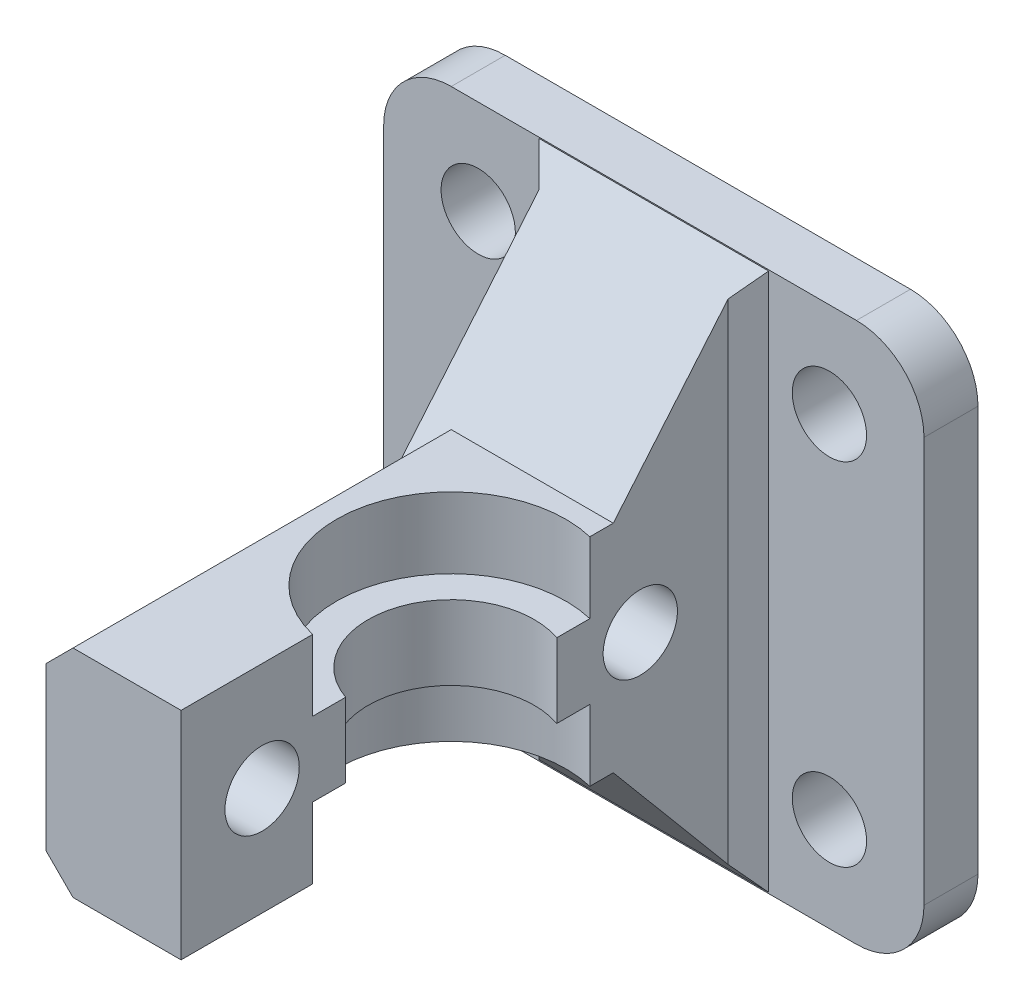
SolidWorks part; units mm, degrees
ref_plane "Front Plane" through (0, 0, 0) normal (0, 0, 1) x (1, 0, 0)
ref_plane "Top Plane" through (0, 0, 0) normal (0, 1, 0) x (1, 0, 0)
ref_plane "Right Plane" through (0, 0, 0) normal (1, 0, 0) x (0, 0, -1)
sketch "Sketch1" plane through (0, 0, 0) normal (0, 0, 1) x (1, 0, 0)
  line L1 (-20, 20) -> (20, 20)
  line L2 (-20, 20) -> (-20, -20)
  line L3 (-20, -20) -> (20, -20)
  line L4 (20, 20) -> (20, -20)
  line L5 (-20, 20) -> (20, -20) construction
  line L6 (-20, -20) -> (20, 20) construction
  point P0 (0, 0)
  dimension "D1" = 40
  dimension "D2" = 40
extrude "Boss-Extrude1" add sketch "Sketch1" along normal blind 4
sketch "Sketch2" plane through (0, 0, 0) normal (0, 0, 1) x (1, 0, 0)
  line L0 (0, 15.4248) -> (0, -21.5401) construction
  line L1 (0, -2.2) -> (0, 2.2) construction
  line L2 (-18.8374, 0) -> (26.7545, 0) construction
  line L3 (2.2, 0) -> (-2.2, 0) construction
  circle A0 centre (-13, 13) radius 2.75
  circle A1 centre (13, 13) radius 2.75
  circle A2 centre (13, -13) radius 2.75
  circle A3 centre (-13, -13) radius 2.75
  dimension "D3" = 5.5
  dimension "D1" = 13
  dimension "D2" = 13
extrude "Cut-Extrude1" cut sketch "Sketch2" along normal up to next
sketch "Sketch3" plane through (0, 0, 0) normal (0, 1, 0) x (1, 0, 0)
  line L0 (-7, -4) -> (-7, -42)
  line L1 (20, -4) -> (-20, -4) construction
  line L2 (-7, -42) -> (3, -42)
  line L3 (0, -21.45) -> (0, 21.45) construction
  line L5 (-7, -4) -> (7, -4)
  line L7 (3, -42) -> (3, -32.2614)
  line L8 (7, -15.7386) -> (7, -4)
  arc A0 (7, -15.7386) -> (3, -32.2614) centre (5, -24) ccw
  dimension "D1" = 8.5
  dimension "D2" = 2
  dimension "D3" = 10
  dimension "D4" = 38
  dimension "D5" = 14
  dimension "D6" = 18
  dimension "D7" = 7
extrude "Boss-Extrude2" add sketch "Sketch3" along normal mid plane 16
chamfer "Chamfer1" distance 10 angle 50 2 edges at (0, -8, 4) (0, 8, 4)
sketch "Sketch4" plane through (0, 0, 0) normal (1, 0, 0) x (0, 0, -1)
  line L0 (22, 0) -> (-22, 0) construction
  line L1 (-4, 19.9175) -> (-4, -19.9175) construction
  circle A0 centre (-12, 0) radius 2.75
  circle A1 centre (-36, 0) radius 2.75
  dimension "D1" = 5.5
  dimension "D2" = 5.5
  dimension "D3" = 8
  dimension "D4" = 32
extrude "Cut-Extrude2" cut sketch "Sketch4" against normal mid plane 14
sketch "Sketch5" plane through (0, 0, 0) normal (0, 1, 0) x (1, 0, 0)
  line L0 (7, -15.7386) -> (7, -18.1843)
  line L1 (3, -29.8157) -> (3, -32.2614)
  line L2 (0, -22) -> (0, 22) construction
  arc A0 (7, -18.1843) -> (3, -29.8157) centre (5, -24) ccw
  arc A1 (7, -15.7386) -> (3, -32.2614) centre (5, -24) ccw
  dimension "D1" = 12.3
  dimension "D2" = 17
  dimension "D3" = 7
  dimension "D4" = 3
extrude "Boss-Extrude3" add sketch "Sketch5" along normal mid plane 5.5
chamfer "Chamfer2" distance 1.5 angle 45 2 edges at (7, 0, 4) (-7, 0, 4)
fillet "Fillet1" radius 5 4 edges at (-20, -20, 2) (20, -20, 2) (20, 20, 2) (-20, 20, 2)
chamfer "Chamfer3" distance 2 angle 45 2 edges at (-7, 8, 28) (-7, -8, 28)
